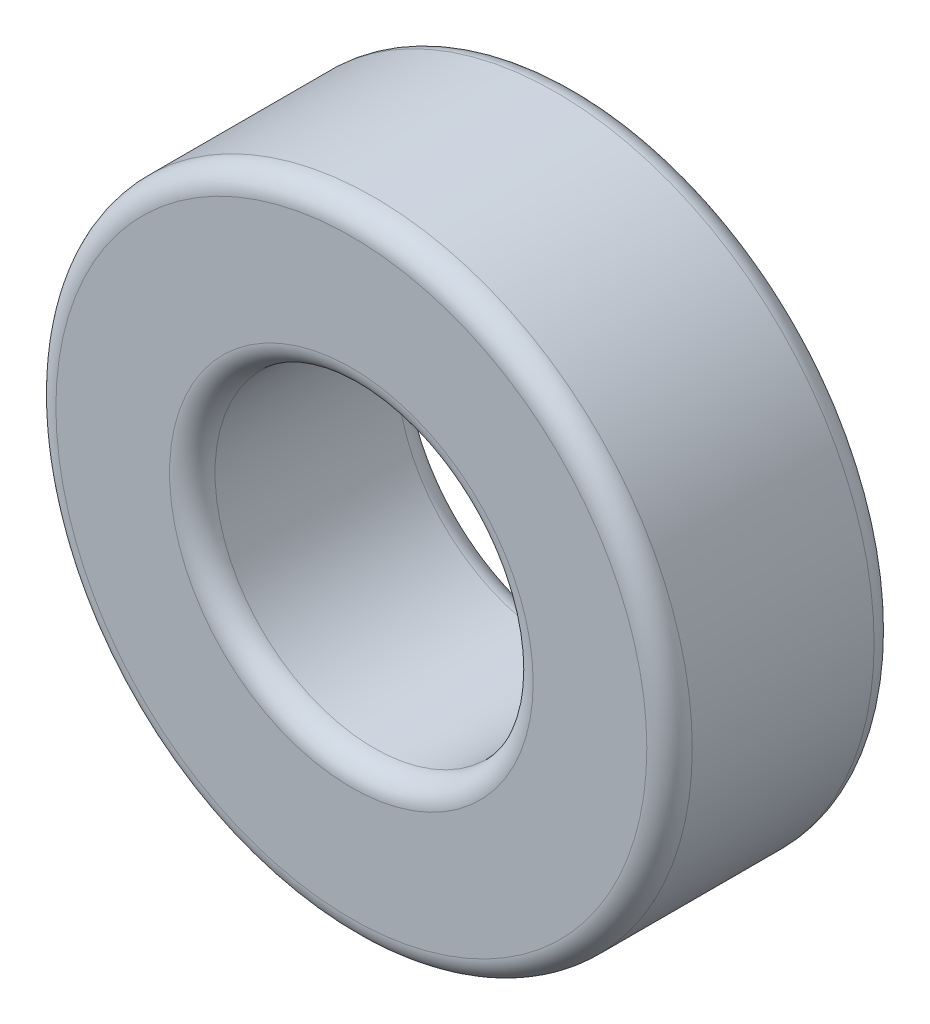
SolidWorks part; units mm, degrees
ref_plane "Plan de face" through (0, 0, 0) normal (0, 0, 1) x (1, 0, 0)
ref_plane "Plan de dessus" through (0, 0, 0) normal (0, 1, 0) x (1, 0, 0)
ref_plane "Plan de droite" through (0, 0, 0) normal (1, 0, 0) x (0, 0, -1)
sketch "Esquisse1" plane through (0, 0, 0) normal (0, 0, 1) x (1, 0, 0)
  circle A0 centre (0, 0) radius 3.5
  circle A1 centre (0, 0) radius 7
  dimension "D1" = 7
  dimension "D2" = 14
extrude "Boss.-Extru.1" add sketch "Esquisse1" along normal blind 5
fillet "Congé1" radius 0.5 4 edges at (3.5, 0, 0) (7, 0, 0) (3.5, 0, 5) (7, 0, 5)
